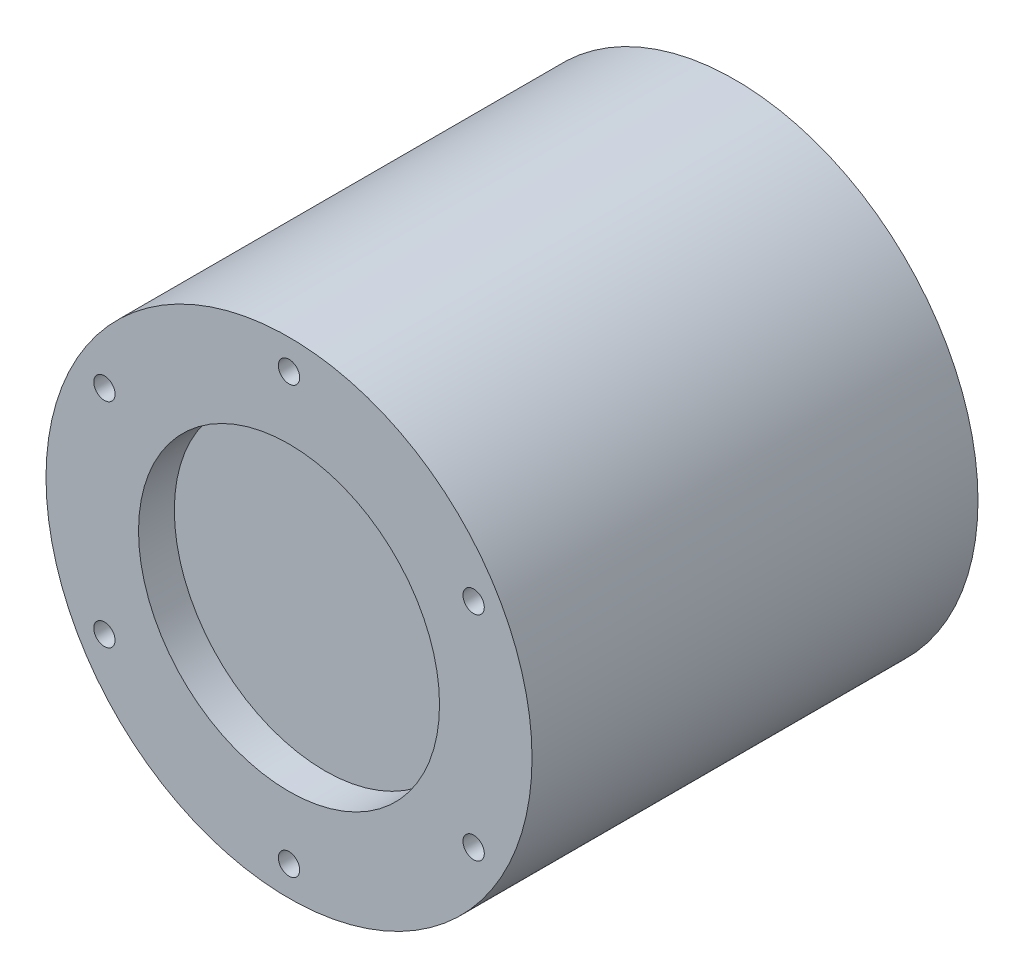
SolidWorks part; units mm, degrees
ref_plane "前视基准面" through (0, 0, 0) normal (0, 0, 1) x (1, 0, 0)
ref_plane "上视基准面" through (0, 0, 0) normal (0, 1, 0) x (1, 0, 0)
ref_plane "右视基准面" through (0, 0, 0) normal (1, 0, 0) x (0, 0, -1)
other "Configuration Table"
sketch "Profile_1" plane through (0, 0, 0) normal (0, 0, 1) x (1, 0, 0)
  circle A0 centre (0, 0) radius 28.5
  circle A1 centre (21.6506, 12.5) radius 1.25
  circle A2 centre (0, 25) radius 1.25
  circle A3 centre (-21.6506, 12.5) radius 1.25
  circle A4 centre (-21.6506, -12.5) radius 1.25
  circle A5 centre (0, -25) radius 1.25
  circle A6 centre (21.6506, -12.5) radius 1.25
extrude "Stator_envelope" add sketch "Profile_1" along normal blind 52.3 from offset 53.3
sketch "Profile_2" plane through (0, 0, 0) normal (0, 0, 1) x (1, 0, 0)
  circle A0 centre (0, 0) radius 17.65
extrude "Rotor_review_recess" cut sketch "Profile_2" along normal blind 4.3 from offset 5.2
